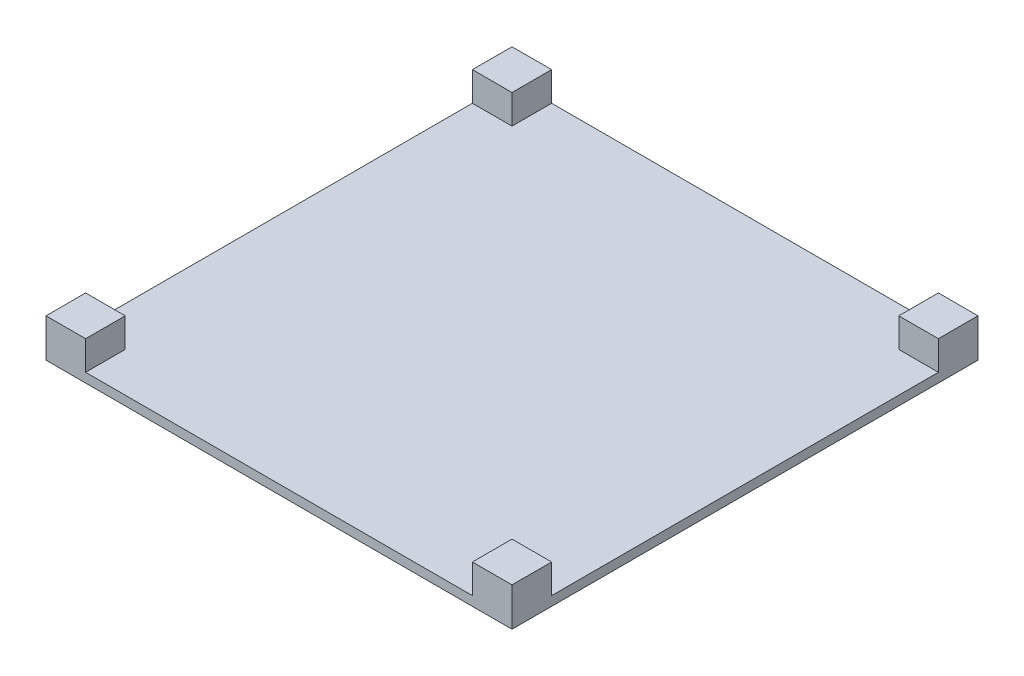
SolidWorks part; units mm, degrees
ref_plane "Front Plane" through (0, 0, 0) normal (0, 0, 1) x (1, 0, 0)
ref_plane "Top Plane" through (0, 0, 0) normal (0, 1, 0) x (1, 0, 0)
ref_plane "Right Plane" through (0, 0, 0) normal (1, 0, 0) x (0, 0, -1)
sketch "Sketch1" plane through (0, 0, 0) normal (0, 1, 0) x (1, 0, 0)
  line L1 (-50, -50) -> (50, -50)
  line L2 (-50, -50) -> (-50, 50)
  line L3 (-50, 50) -> (50, 50)
  line L4 (50, -50) -> (50, 50)
  line L5 (-50, -50) -> (50, 50) construction
  line L6 (-50, 50) -> (50, -50) construction
  point P0 (0, 0)
  point P6 (40.1172, -38.0317)
  point P7 (0, 0)
  point P8 (11.9205, -11.62)
  point P9 (0, 0)
  point P10 (0, 0)
  point P11 (48.799, -50.5718)
extrude "Boss-Extrude2" add sketch "Sketch1" along normal blind 2
sketch "Sketch3" plane through (0, 2, 0) normal (0, 1, 0) x (1, 0, 0)
  line L1 (50, -50) -> (41.5, -50)
  line L2 (50, -50) -> (50, -41.5)
  line L3 (50, -41.5) -> (41.5, -41.5)
  line L4 (41.5, -50) -> (41.5, -41.5)
  line L5 (-50, -50) -> (-41.5, -50)
  line L6 (-50, -50) -> (-50, -41.5)
  line L7 (-50, -41.5) -> (-41.5, -41.5)
  line L8 (-41.5, -50) -> (-41.5, -41.5)
  line L9 (50, 50) -> (41.5, 50)
  line L10 (50, 50) -> (50, 41.5)
  line L11 (50, 41.5) -> (41.5, 41.5)
  line L12 (41.5, 50) -> (41.5, 41.5)
  line L13 (-50, 50) -> (-41.5, 50)
  line L14 (-50, 50) -> (-50, 41.5)
  line L15 (-50, 41.5) -> (-41.5, 41.5)
  line L16 (-41.5, 50) -> (-41.5, 41.5)
extrude "Boss-Extrude4" add sketch "Sketch3" along normal blind 6.25
